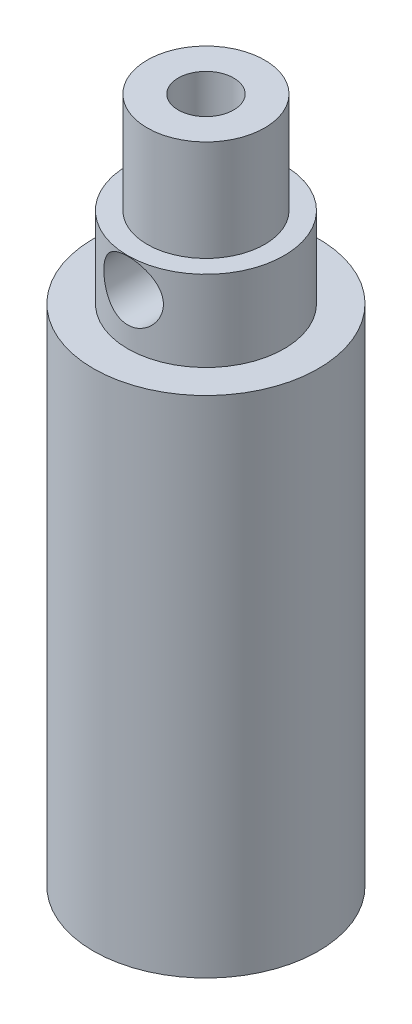
SolidWorks part; units mm, degrees
ref_plane "Front Plane" through (0, 0, 0) normal (0, 0, 1) x (1, 0, 0)
ref_plane "Top Plane" through (0, 0, 0) normal (0, 1, 0) x (1, 0, 0)
ref_plane "Right Plane" through (0, 0, 0) normal (1, 0, 0) x (0, 0, -1)
sketch "Sketch1" plane through (0, 0, 0) normal (0, 1, 0) x (1, 0, 0)
  circle A0 centre (0, 0) radius 11.15
  dimension "60" = 22.3
extrude "Boss-Extrude1" add sketch "Sketch1" along normal blind 50
sketch "Sketch2" plane through (0, 50, 0) normal (0, 1, 0) x (1, 0, 0)
  circle A0 centre (0, 0) radius 7.75
  dimension "D1" = 15.5
extrude "Boss-Extrude2" add sketch "Sketch2" along normal blind 8
sketch "Sketch3" plane through (0, 58, 0) normal (0, 1, 0) x (1, 0, 0)
  circle A0 centre (0, 0) radius 5.825
  dimension "D1" = 11.65
extrude "Boss-Extrude3" add sketch "Sketch3" along normal blind 10
sketch "Sketch4" plane through (0, 0, 0) normal (0, -1, 0) x (1, 0, 0)
  circle A0 centre (0, 0) radius 9.1
  dimension "D1" = 18.2
extrude "Cut-Extrude1" cut sketch "Sketch4" against normal offset from surface (35 mm away) 15 up to face at (0, 50, 7.75)
sketch "Sketch5" plane through (0, 68, 0) normal (0, 1, 0) x (1, 0, 0)
  circle A0 centre (0, 0) radius 2.75
  dimension "D1" = 5.5
extrude "Cut-Extrude2" cut sketch "Sketch5" against normal through all
sketch "Sketch10" plane through (0, 58, 0) normal (0, 1, 0) x (1, 0, 0)
  line L1 (0, -7.75) -> (3, -7.75)
  line L2 (0, -7.75) -> (0, -19.1928)
  line L3 (0, -19.1928) -> (3, -19.1928)
  line L4 (3, -7.75) -> (3, -19.1928)
  line L5 (0, -7.75) -> (-3, -7.75)
  line L6 (0, -7.75) -> (0, -19.1928)
  line L7 (0, -19.1928) -> (-3, -19.1928)
  line L8 (-3, -7.75) -> (-3, -19.1928)
  circle A0 centre (0, 0) radius 7.75 construction
  dimension "D1" = 3
extrude "Boss-Extrude5" add sketch "Sketch10" against normal blind 6 separate body contours L5 L8 L7 L2 | L4 L1 L2 L3
sketch "Sketch11" plane through (0, 0, 19.1928) normal (0, 0, 1) x (1, 0, 0)
  line L0 (-3, 55) -> (3, 55)
  line L1 (-3, 52) -> (-3, 58) construction
  line L2 (3, 52) -> (3, 58) construction
  circle A0 centre (0, 55) radius 2.95
  dimension "D1" = 5.9
sketch "Sketch12" plane through (0, 58, 0) normal (0, 1, 0) x (1, 0, 0)
  line L0 (3, -7.75) -> (3, -19.1928) construction
  line L1 (-3, -7.75) -> (3, -7.75)
  line L2 (-3, -7.75) -> (-3, -8.75)
  line L3 (-3, -8.75) -> (3, -8.75)
  line L4 (3, -7.75) -> (3, -8.75)
  dimension "1" = 1
extrude "Cut-Extrude6" cut sketch "Sketch12" against normal up to body (6 mm away)
extrude "Cut-Extrude8" cut sketch "Sketch11" against normal blind 18 contours L0 A0 | L0 A0
sketch "Sketch14" plane through (0, 58, 0) normal (0, 1, 0) x (1, 0, 0)
  line L0 (3, -8.75) -> (3, -19.1928) construction
  line L1 (-3, -8.75) -> (3, -8.75)
  line L2 (-3, -8.75) -> (-3, -19.1928)
  line L3 (-3, -19.1928) -> (3, -19.1928)
  line L4 (3, -8.75) -> (3, -19.1928)
extrude "Cut-Extrude9" cut sketch "Sketch14" against normal up to surface (8 mm away) up to face at (0, 50, 7.75)
